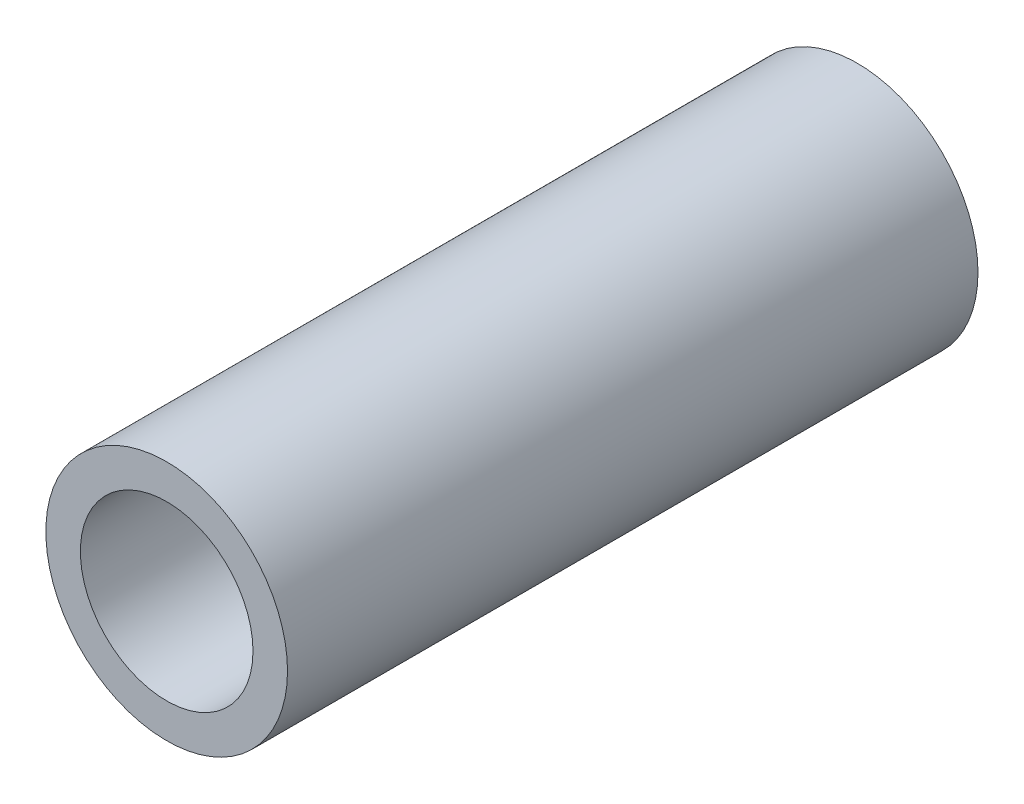
SolidWorks part; units mm, degrees
material "1060 Alaşım"
ref_plane "Ön Düzlem" through (0, 0, 0) normal (0, 0, 1) x (1, 0, 0)
ref_plane "Üst Düzlem" through (0, 0, 0) normal (0, 1, 0) x (1, 0, 0)
ref_plane "Sağ Düzlem" through (0, 0, 0) normal (1, 0, 0) x (0, 0, -1)
sketch "Çizim1" plane through (0, 0, 0) normal (0, 0, 1) x (1, 0, 0)
  circle A0 centre (0, 0) radius 7.5
  circle A1 centre (0, 0) radius 10.5
  dimension "D1" = 15
  dimension "D2" = 21
extrude "Yükseklik-Ekstrüzyon1" add sketch "Çizim1" along normal mid plane 60
